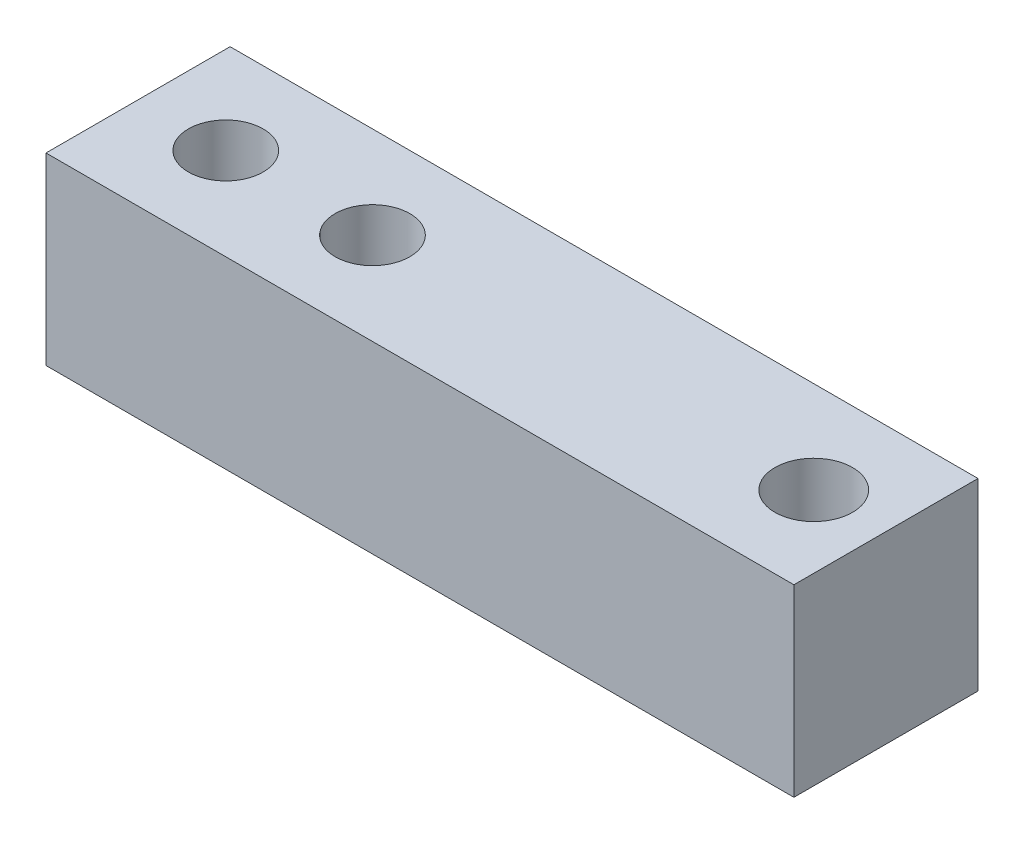
SolidWorks part; units mm, degrees
ref_plane "Front Plane" through (0, 0, 0) normal (0, 0, 1) x (1, 0, 0)
ref_plane "Top Plane" through (0, 0, 0) normal (0, 1, 0) x (1, 0, 0)
ref_plane "Right Plane" through (0, 0, 0) normal (1, 0, 0) x (0, 0, -1)
sketch "Sketch1" plane through (0, 0, 0) normal (0, 1, 0) x (1, 0, 0)
  line L1 (-65, 16) -> (65, 16)
  line L2 (-65, 16) -> (-65, -16)
  line L3 (-65, -16) -> (65, -16)
  line L4 (65, 16) -> (65, -16)
  line L5 (-65, 16) -> (65, -16) construction
  line L6 (-65, -16) -> (65, 16) construction
  point P0 (0, 0)
  dimension "D1" = 130
  dimension "D2" = 32
extrude "Boss-Extrude1" add sketch "Sketch1" along normal blind 32
sketch "Sketch2" plane through (0, 32, 0) normal (0, 1, 0) x (1, 0, 0)
  line L0 (-65, 0) -> (65, 0) construction
  line L1 (-65, 16) -> (-65, -16) construction
  line L2 (65, -16) -> (65, 16) construction
  circle A0 centre (-49.75, 0) radius 6.5
  circle A1 centre (-24.25, 0) radius 6.5
  circle A2 centre (52.45, 0) radius 6.75
  dimension "D1" = 13.5
  dimension "D3" = 15.25
  dimension "D4" = 13
  dimension "D5" = 13
  dimension "D6" = 25.5
  dimension "D2" = 12.55
extrude "Cut-Extrude1" cut sketch "Sketch2" against normal blind 32
